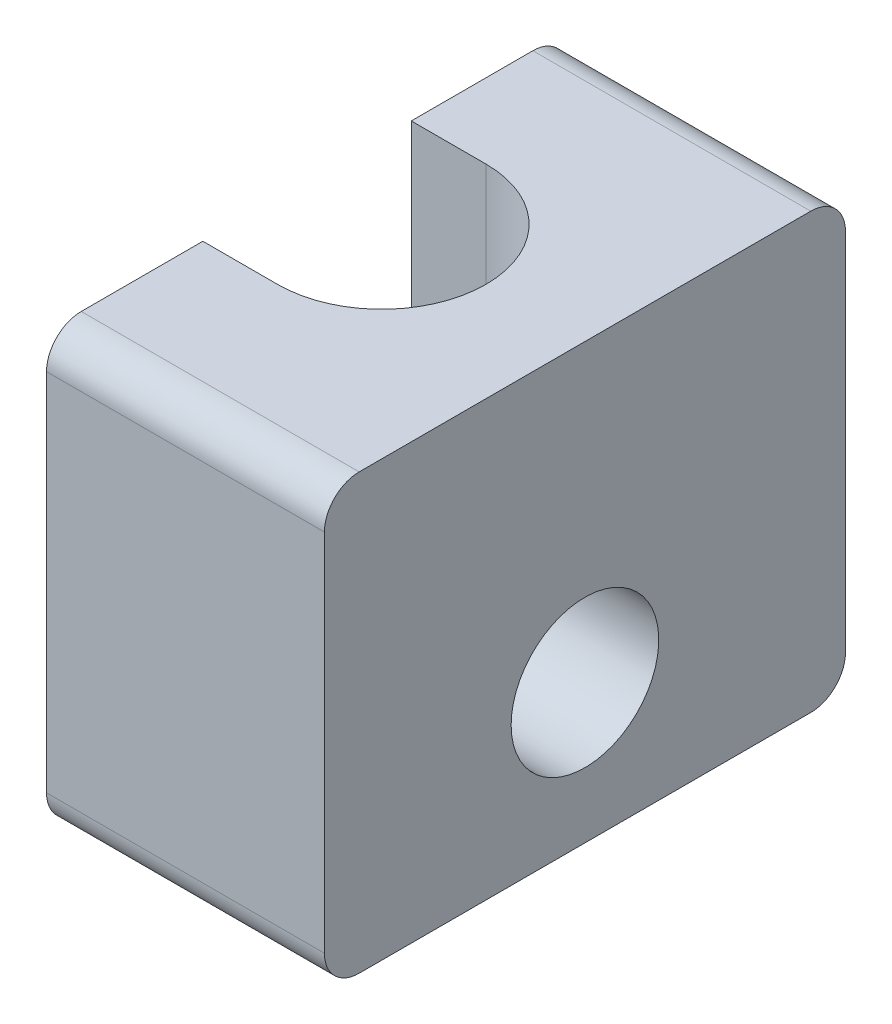
SolidWorks part; units mm, degrees
ref_plane "Front" through (0, 0, 0) normal (0, 0, 1) x (1, 0, 0)
ref_plane "Top" through (0, 0, 0) normal (0, 1, 0) x (1, 0, 0)
ref_plane "Right" through (0, 0, 0) normal (1, 0, 0) x (0, 0, -1)
sketch "Sketch1" plane through (0, 0, 0) normal (0, 1, 0) x (1, 0, 0)
  line L1 (-8, 15) -> (8, 15)
  line L2 (-8, 15) -> (-8, -15)
  line L3 (-8, -15) -> (8, -15)
  line L4 (8, 15) -> (8, -15)
  line L5 (-8, 15) -> (8, -15) construction
  line L6 (-8, -15) -> (8, 15) construction
  point P0 (0, 0)
  dimension "D1" = 16
  dimension "D2" = 30
extrude "Boss-Extrude1" add sketch "Sketch1" along normal blind 25
sketch "Sketch2" plane through (0, 25, 0) normal (0, 1, 0) x (1, 0, 0)
  line L0 (-8, 0) -> (-3.7, 0) construction
  line L1 (-8, 15) -> (-8, -15) construction
  line L2 (-8, 6) -> (-3.7, 6)
  line L3 (-8, -6) -> (-3.7, -6)
  arc A0 (-8, 6) -> (-8, -6) centre (-8, 0) ccw
  arc A1 (-3.7, -6) -> (-3.7, 6) centre (-3.7, 0) ccw
  point P5 (-5.85, 0)
  dimension "D1" = 6
  dimension "D2" = 4.3
extrude "Cut-Extrude1" cut sketch "Sketch2" against normal blind 10
sketch "Sketch3" plane through (-8, 0, 0) normal (-1, 0, 0) x (0, 0, 1)
  line L0 (-15, 16) -> (15, 16) construction
  line L1 (-15, 25) -> (-15, 0) construction
  line L2 (15, 25) -> (15, 0) construction
  line L3 (15, 16) -> (-15, 0) construction
  line L4 (-15, 16) -> (15, 0) construction
  line L5 (-15, 0) -> (15, 0) construction
  circle A0 centre (0, 8) radius 4.25
  dimension "D1" = 8.5
  dimension "D2" = 8
extrude "Cut-Extrude2" cut sketch "Sketch3" against normal through all
fillet "Fillet1" radius 2 4 edges at (0, 0, 15) (0, 0, -15) (0, 25, 15) (0, 25, -15)
